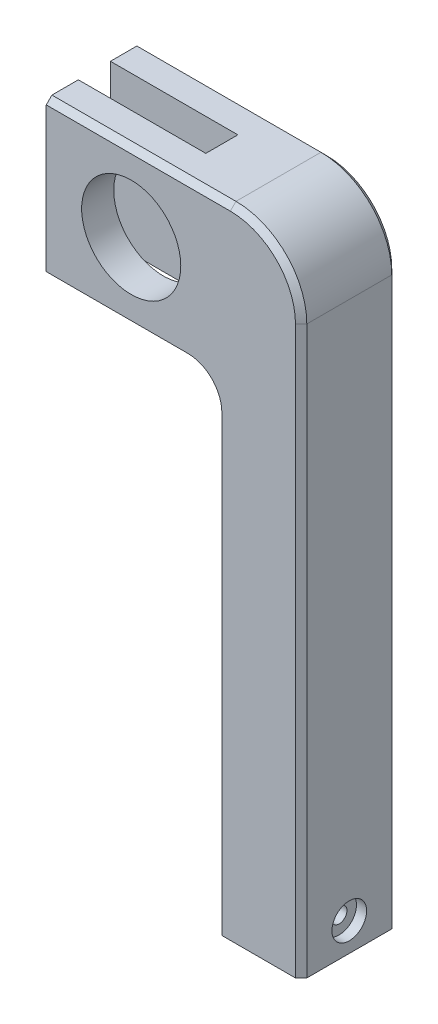
SolidWorks part; units mm, degrees
ref_plane "Front Plane" through (0, 0, 0) normal (0, 0, 1) x (1, 0, 0)
ref_plane "Top Plane" through (0, 0, 0) normal (0, 1, 0) x (1, 0, 0)
ref_plane "Right Plane" through (0, 0, 0) normal (1, 0, 0) x (0, 0, -1)
sketch "Sketch1" plane through (0, 0, 0) normal (0, 0, 1) x (1, 0, 0)
  line L0 (0, 0) -> (-30, 0)
  line L9 (-30, 170) -> (-30, 0)
  line L10 (-30, 170) -> (-90, 170)
  line L11 (-90, 170) -> (-90, 225)
  line L12 (-90, 225) -> (0, 225)
  line L13 (0, 225) -> (0, 0)
  dimension "D1" = 225
  dimension "D2" = 90
  dimension "D3" = 30
  dimension "D4" = 55
extrude "Boss-Extrude1" add sketch "Sketch1" against normal mid plane 34
sketch "Sketch3" plane through (0, 225, 0) normal (0, 1, 0) x (1, 0, 0)
  line L0 (-90, 17) -> (-90, -17) construction
  line L1 (-45, -5.665) -> (-90, -5.665)
  line L2 (-45, -5.665) -> (-45, 5.665)
  line L3 (-45, 5.665) -> (-90, 5.665)
  line L4 (-90, -5.665) -> (-90, 5.665)
  line L5 (-45, -5.665) -> (-90, 5.665) construction
  line L6 (-45, 5.665) -> (-90, -5.665) construction
  line L7 (-90, 0) -> (0, 0) construction
  point P0 (-67.5, 0)
  dimension "D1" = 11.33
  dimension "D2" = 45
extrude "Cut-Extrude1" cut sketch "Sketch3" against normal up to next
fillet "Fillet1" radius 25 1 edges at (0, 225, 0)
fillet "Fillet2" radius 10 1 edges at (-30, 170, 0)
sketch "Sketch4" plane through (0, 0, 17) normal (0, 0, 1) x (1, 0, 0)
  line L0 (-90, 225) -> (-90, 170) construction
  line L1 (-90, 197.5) -> (-39.4804, 197.5) construction
  circle A0 centre (-60, 197.5) radius 17.5
  dimension "D2" = 35
  dimension "D1" = 30
extrude "Cut-Extrude2" cut sketch "Sketch4" against normal up to surface (11.335 mm away) up to face at (-67.5, 197.5, 5.665)
sketch "Sketch5" plane through (0, 0, -17) normal (0, 0, -1) x (-1, 0, 0)
  line L0 (90, 197.5) -> (42.6224, 197.5) construction
  line L1 (90, 225) -> (90, 170) construction
  circle A0 centre (60, 197.5) radius 11.375
  dimension "D1" = 30
  dimension "D2" = 22.75
extrude "Cut-Extrude3" cut sketch "Sketch5" against normal up to next
chamfer "Chamfer1" distance 2 angle 45 12 edges at (-65, 170, 17) (-32.9289, 167.0711, 17) (-30, 80, 17) (-65, 170, -17) (-32.9289, 167.0711, -17) (-30, 80, -17) (-57.5, 225, -17) (-7.3223, 217.6777, -17) (0, 100, -17) (-57.5, 225, 17) (-7.3223, 217.6777, 17) (0, 100, 17)
sketch "Sketch9" plane through (0, 0, 0) normal (1, 0, 0) x (0, 0, -1)
  line L0 (0, 0) -> (0, 10) construction
  line L1 (15, 0) -> (-15, 0) construction
  point P1 (0, 10)
  dimension "D1" = 10
hole_wizard "CBORE for M5 Hex Head Bolt1" positions "Sketch9" profile "Sketch10" counterbore size "M5" standard "ANSI Metric" end condition up to next
sketch "Sketch10" plane through (0, 10, 0) normal (0, 1, 0) x (0, 0, -1)
  line L0 (0, 0) -> (0, 30)
  line L1 (0, 30) -> (2.75, 30)
  line L3 (2.75, 30) -> (2.75, 3.58)
  line L4 (2.75, 3.58) -> (6.12, 3.58)
  line L5 (6.12, 3.58) -> (6.12, 0)
  line L7 (6.12, 0) -> (0, 0)
  line L11 (0, -6.35) -> (0, 107.95) construction
  dimension "Thru Hole Dia." = 5.5
  dimension "Thru Hole Depth" = 30
  dimension "C'Bore Dia." = 12.24
  dimension "C'Bore Depth" = 3.58
sketch "Sketch11" plane through (-90, 0, 0) normal (-1, 0, 0) x (0, 0, 1)
  line L0 (-15, 170) -> (-5.665, 170) construction
  line L1 (-11.33, 175) -> (11.33, 175) construction
  line L2 (-11.33, 175) -> (-11.33, 220) construction
  line L3 (-11.33, 220) -> (11.33, 220) construction
  line L4 (11.33, 175) -> (11.33, 220) construction
  line L5 (-11.33, 175) -> (11.33, 220) construction
  line L6 (-11.33, 220) -> (11.33, 175) construction
  line L7 (17, 223) -> (17, 172) construction
  line L8 (-17, 223) -> (-17, 172) construction
  point P1 (11.33, 220)
  point P2 (-11.33, 175)
  point P3 (-11.33, 220)
  point P4 (11.33, 175)
  dimension "D1" = 45
  dimension "D2" = 5
  dimension "D3" = 5.67
  dimension "D4" = 5.67
hole_wizard "Ø3.0mm Dowel Hole1" positions "Sketch11" profile "Sketch12" hole size "Ø3.0" standard "ANSI Metric"
sketch "Sketch12" plane through (-90, 220, 11.33) normal (0, 1, 0) x (0, 0, 1)
  line L0 (0, 0) -> (0, 20.9013)
  line L1 (0, 20.9013) -> (1.5, 20)
  line L2 (1.5, 20) -> (1.5, 0)
  line L5 (1.5, 0) -> (0, 0)
  line L10 (0, 20.9013) -> (-1.5, 20) construction
  line L11 (0, -6.35) -> (0, 107.95) construction
  dimension "Hole Dia." = 3
  dimension "Hole Depth" = 20
  dimension "Drill Angle" = 118
